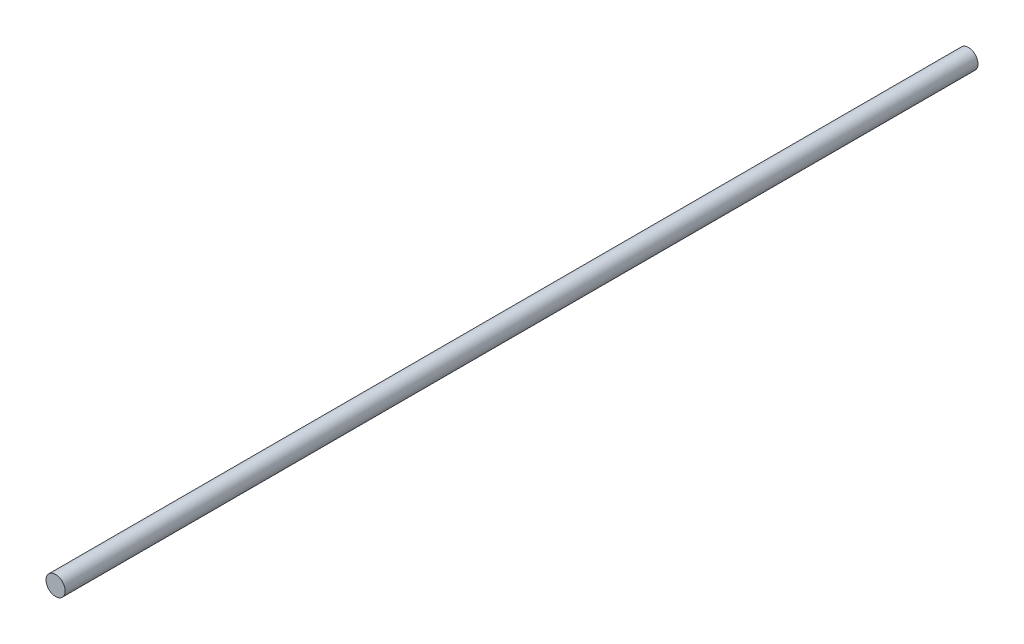
SolidWorks part; units mm, degrees
ref_plane "Front" through (0, 0, 0) normal (0, 0, 1) x (1, 0, 0)
ref_plane "Top" through (0, 0, 0) normal (0, 1, 0) x (1, 0, 0)
ref_plane "Right" through (0, 0, 0) normal (1, 0, 0) x (0, 0, -1)
sketch "Sketch1" plane through (0, 0, 0) normal (0, 0, 1) x (1, 0, 0)
  circle A0 centre (0, 0) radius 4
  dimension "D1" = 8
extrude "Boss-Extrude1" add sketch "Sketch1" along normal blind 381.12
equation "\"linear-thread-dia\"= 8mm ' Diameter of the metal threaded rod used on the X Axis"
equation "\"baseplate-height\"= 360mm"
equation "\"baseplate-width\"= 290mm"
equation "\"material-thickness\"= 12.4mm"
equation "\"nut_depth\"= 4.76mm"
equation "\"stepper_clearance\"= 32mm"
equation "\"rod_length_yaxis\"= \"baseplate-width\" + ( \"material-thickness\" * 4 ) + ( \"nut_depth\" * 2 ) + \"stepper_clearance\""
equation "\"D1@Boss-Extrude1\"= \"rod_length_yaxis\""
equation "\"D1@Sketch1\"= \"linear-thread-dia\""
